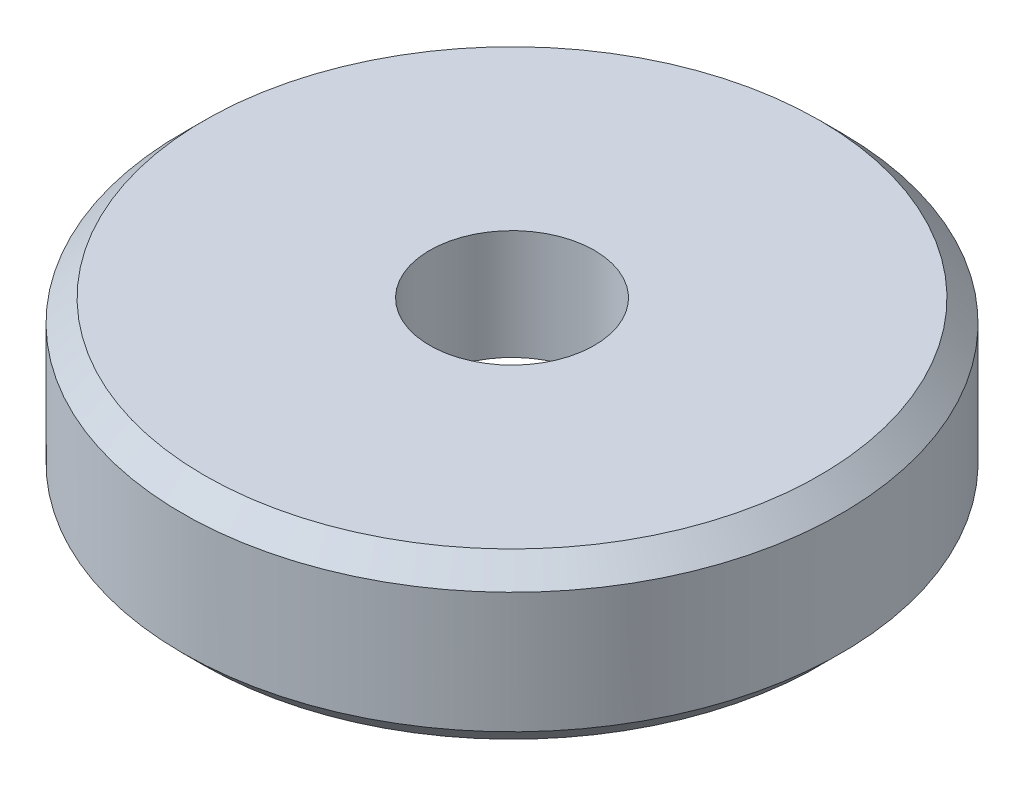
SolidWorks part; units mm, degrees
material "6061-T6 (SS)"
ref_plane "Front" through (0, 0, 0) normal (0, 0, 1) x (1, 0, 0)
ref_plane "Top" through (0, 0, 0) normal (0, 1, 0) x (1, 0, 0)
ref_plane "Right" through (0, 0, 0) normal (1, 0, 0) x (0, 0, -1)
sketch "Sketch1" plane through (0, 0, 0) normal (0, 1, 0) x (1, 0, 0)
  circle A0 centre (0, 0) radius 38.1
  circle A1 centre (0, 0) radius 9.525
  dimension "D1" = 76.2
  dimension "D2" = 19.05
extrude "Boss-Extrude1" add sketch "Sketch1" along normal blind 19.05
chamfer "Chamfer1" distance 2.54 angle 45 2 edges at (0, 0, 38.1) (0, 19.05, 38.1)
sketch "Sketch2" plane through (0, 19.05, 0) normal (0, 1, 0) x (1, 0, 0)
  circle A0 centre (0, 0) radius 19.05
  dimension "D1" = 38.1
extrude "Cut-Extrude1" [suppressed] cut sketch "Sketch2" against normal blind 12.7
sketch "Sketch3" plane through (0, 0, 0) normal (0, -1, 0) x (-1, 0, 0)
  circle A0 centre (0, 0) radius 25.4
  dimension "D1" = 50.8
extrude "Cut-Extrude2" cut sketch "Sketch3" against normal blind 6.35
sketch "Sketch4" plane through (0, 19.05, 0) normal (0, 1, 0) x (1, 0, 0)
  circle A0 centre (0, 0) radius 12.7
  dimension "D1" = 25.4
split line "Split Line1" [suppressed]
